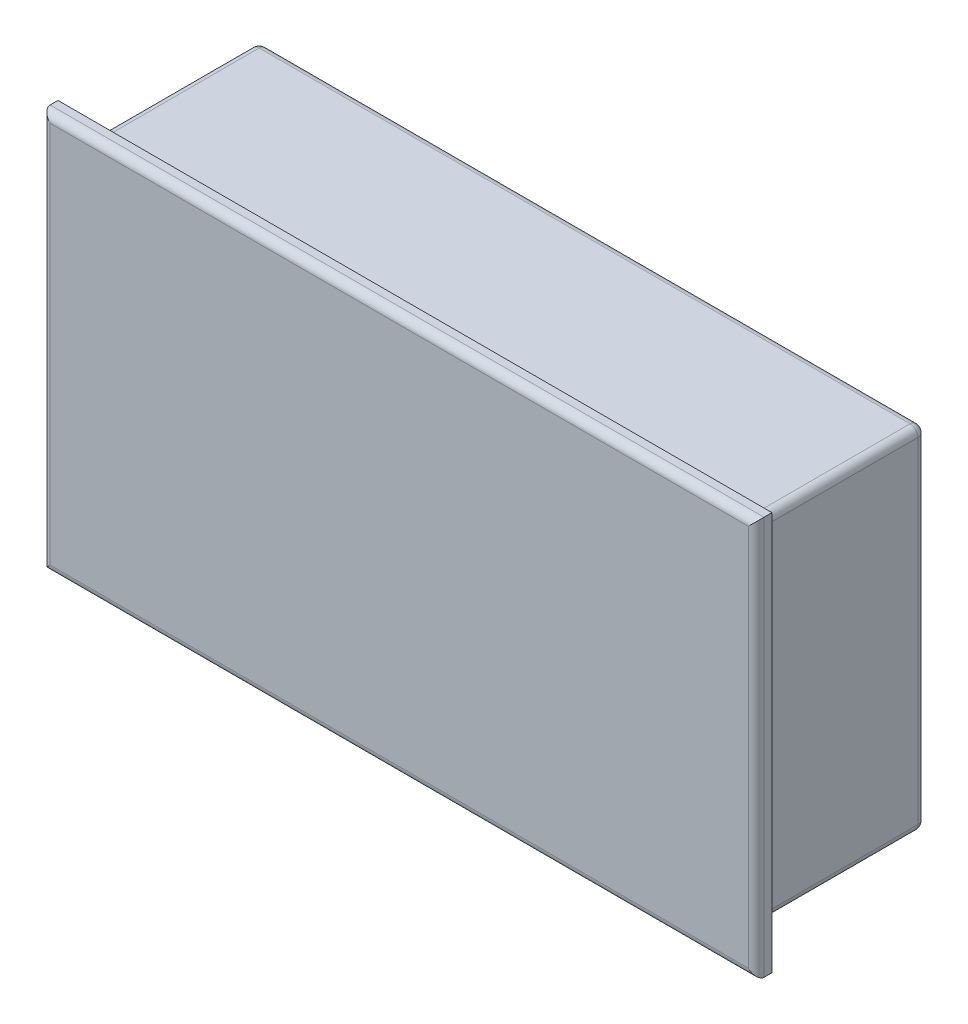
SolidWorks part; units mm, degrees
ref_plane "Front Plane" through (0, 0, 0) normal (0, 0, 1) x (1, 0, 0)
ref_plane "Top Plane" through (0, 0, 0) normal (0, 1, 0) x (1, 0, 0)
ref_plane "Right Plane" through (0, 0, 0) normal (1, 0, 0) x (0, 0, -1)
sketch "Sketch1" plane through (0, 0, 0) normal (0, 0, 1) x (1, 0, 0)
  line L1 (-42.25, 22.25) -> (42.25, 22.25)
  line L2 (-42.25, 22.25) -> (-42.25, -22.25)
  line L3 (-42.25, -22.25) -> (42.25, -22.25)
  line L4 (42.25, 22.25) -> (42.25, -22.25)
  line L5 (-42.25, 22.25) -> (42.25, -22.25) construction
  line L6 (-42.25, -22.25) -> (42.25, 22.25) construction
  point P0 (0, 0)
  dimension "D1" = 44.5
  dimension "D2" = 84.5
extrude "Boss-Extrude1" add sketch "Sketch1" against normal blind 22.5
sketch "Sketch2" plane through (0, 0, 0) normal (0, 0, 1) x (1, 0, 0)
  line L0 (-42.25, 22.25) -> (-42.25, -22.25) construction
  line L1 (45.25, -25.25) -> (-45.25, -25.25)
  line L2 (45.25, -25.25) -> (45.25, 25.25)
  line L3 (45.25, 25.25) -> (-45.25, 25.25)
  line L4 (-45.25, -25.25) -> (-45.25, 25.25)
  line L5 (45.25, -25.25) -> (-45.25, 25.25) construction
  line L6 (45.25, 25.25) -> (-45.25, -25.25) construction
  line L7 (42.25, 22.25) -> (-42.25, 22.25) construction
  point P0 (0, 0)
  dimension "D1" = 3
  dimension "D2" = 3
extrude "Boss-Extrude2" add sketch "Sketch2" along normal blind 2
fillet "Fillet1" radius 1 12 edges at (0, 22.25, -22.5) (-42.25, 0, -22.5) (0, -22.25, -22.5) (42.25, 0, -22.5) (0, 25.25, 2) (45.25, 0, 2) (0, -25.25, 2) (-45.25, 0, 2) (-42.25, -22.25, -11.25) (42.25, 22.25, -11.25) (42.25, -22.25, -11.25) (-42.25, 22.25, -11.25)
